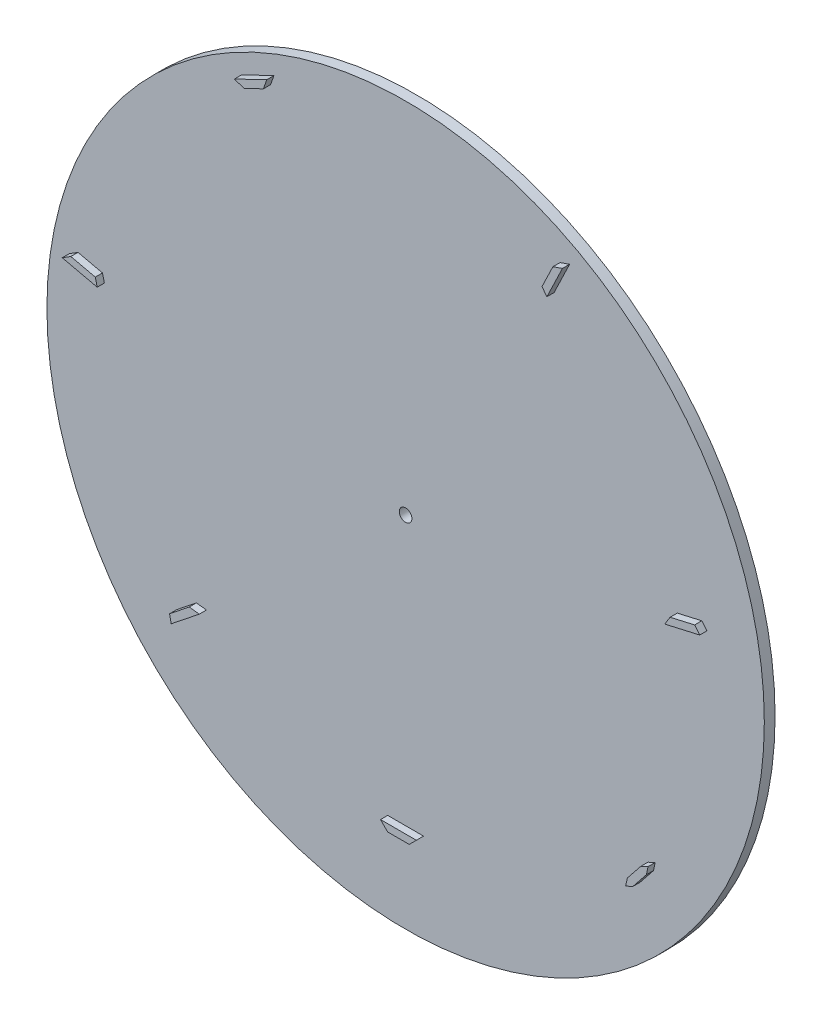
SolidWorks part; units mm, degrees
ref_plane "Front Plane" through (0, 0, 0) normal (0, 0, 1) x (1, 0, 0)
ref_plane "Top Plane" through (0, 0, 0) normal (0, 1, 0) x (1, 0, 0)
ref_plane "Right Plane" through (0, 0, 0) normal (1, 0, 0) x (0, 0, -1)
sketch "Sketch1" plane through (0, 0, 0) normal (0, 0, 1) x (1, 0, 0)
  circle A0 centre (0, 0) radius 100
  circle A1 centre (0, 0) radius 1.75
  dimension "D1" = 200
  dimension "D2" = 3.5
extrude "Boss-Extrude1" add sketch "Sketch1" along normal blind 3
sketch "Sketch2" plane through (0, 0, 3) normal (0, 0, 1) x (1, 0, 0)
  line L0 (0, 0) -> (0, -100) construction
  line L1 (0, 0) -> (-17.8557, -98.393) construction
  line L2 (0, 0) -> (-35.1375, -93.6235) construction
  line L3 (0, 0) -> (-51.2899, -85.8449) construction
  line L4 (0, 0) -> (-65.7939, -75.3071) construction
  line L5 (0, 0) -> (-78.1831, -62.349) construction
  line L6 (0, 0) -> (-88.0596, -47.3869) construction
  line L7 (0, 0) -> (-95.1057, -30.9017) construction
  line L8 (0, 0) -> (-99.095, -13.4233) construction
  line L9 (0, 0) -> (-99.8993, 4.4865) construction
  line L10 (0, 0) -> (-97.4928, 22.2521) construction
  line L11 (0, 0) -> (-91.9528, 39.3025) construction
  line L12 (0, 0) -> (-83.4573, 55.0897) construction
  line L13 (0, 0) -> (-72.2795, 69.1063) construction
  line L14 (0, 0) -> (-58.7785, 80.9017) construction
  line L15 (0, 0) -> (-43.3884, 90.0969) construction
  line L16 (0, 0) -> (-26.6037, 96.3963) construction
  line L17 (0, 0) -> (-8.9639, 99.5974) construction
  line L18 (0, 0) -> (8.9639, 99.5974) construction
  line L19 (0, 0) -> (26.6037, 96.3963) construction
  line L20 (0, 0) -> (43.3884, 90.0969) construction
  line L21 (0, 0) -> (58.7785, 80.9017) construction
  line L22 (0, 0) -> (72.2795, 69.1063) construction
  line L23 (0, 0) -> (83.4573, 55.0897) construction
  line L24 (0, 0) -> (91.9528, 39.3025) construction
  line L25 (0, 0) -> (97.4928, 22.2521) construction
  line L26 (0, 0) -> (99.8993, 4.4865) construction
  line L27 (0, 0) -> (99.095, -13.4233) construction
  line L28 (0, 0) -> (95.1057, -30.9017) construction
  line L29 (0, 0) -> (88.0596, -47.3869) construction
  line L30 (0, 0) -> (78.1831, -62.349) construction
  line L31 (0, 0) -> (65.7939, -75.3071) construction
  line L32 (0, 0) -> (51.2899, -85.8449) construction
  line L33 (0, 0) -> (35.1375, -93.6235) construction
  line L34 (0, 0) -> (17.8557, -98.393) construction
  line L35 (3, -77) -> (5, -75)
  line L36 (-5, -75) -> (5, -75)
  line L37 (-5, -75) -> (-5, -95) construction
  line L38 (-5, -95) -> (5, -95)
  line L39 (5, -75) -> (5, -95) construction
  line L40 (-3, -77) -> (3, -77)
  line L42 (-3, -93) -> (3, -93)
  line L44 (-3, -84) -> (3, -84)
  line L45 (-3, -84) -> (-3, -86) construction
  line L46 (-3, -86) -> (3, -86)
  line L47 (3, -84) -> (3, -86) construction
  line L48 (-3, -77) -> (-5, -75)
  line L49 (-3, -93) -> (-5, -95)
  line L50 (3, -93) -> (5, -95)
  line L51 (-3, -84) -> (-5, -85)
  line L52 (-5, -85) -> (-3, -86)
  line L53 (3, -84) -> (5, -85)
  line L54 (5, -85) -> (3, -86)
  line L55 (-3, -77) -> (-3, -84)
  line L56 (3, -77) -> (3, -84)
  line L57 (-3, -93) -> (-3, -86)
  line L58 (3, -93) -> (3, -86)
  line L59 (-5, -75) -> (-5, -85)
  line L60 (-5, -95) -> (-5, -85)
  line L61 (5, -75) -> (5, -85)
  line L62 (5, -95) -> (5, -85)
  line L63 (-61.7548, -42.8526) -> (-55.5199, -50.6709)
  line L64 (-61.7548, -42.8526) -> (-69.5731, -49.0875)
  line L65 (-62.0715, -45.6632) -> (-61.7548, -42.8526)
  line L66 (-62.0715, -45.6632) -> (-58.3306, -50.3542)
  line L67 (-58.3306, -50.3542) -> (-55.5199, -50.6709)
  line L68 (-55.5199, -50.6709) -> (-63.3382, -56.9058)
  line L69 (-58.3306, -50.3542) -> (-63.8034, -54.7186)
  line L70 (-62.0715, -45.6632) -> (-67.5443, -50.0276)
  line L71 (-67.5443, -50.0276) -> (-69.5731, -49.0875)
  line L72 (-69.5731, -49.0875) -> (-69.108, -51.2746)
  line L73 (-67.5443, -50.0276) -> (-63.8034, -54.7186)
  line L74 (-69.108, -51.2746) -> (-65.367, -55.9656)
  line L75 (-77.3914, -55.3224) -> (-69.5731, -49.0875)
  line L76 (-74.5808, -55.6391) -> (-69.108, -51.2746)
  line L77 (-74.5808, -55.6391) -> (-77.3914, -55.3224)
  line L78 (-77.3914, -55.3224) -> (-71.1565, -63.1407)
  line L79 (-74.5808, -55.6391) -> (-70.8399, -60.33)
  line L80 (-70.8399, -60.33) -> (-65.367, -55.9656)
  line L81 (-63.8034, -54.7186) -> (-63.3382, -56.9058)
  line L82 (-63.3382, -56.9058) -> (-65.367, -55.9656)
  line L83 (-71.1565, -63.1407) -> (-63.3382, -56.9058)
  line L84 (-70.8399, -60.33) -> (-71.1565, -63.1407)
  line L85 (-72.007, 21.5637) -> (-74.2322, 11.8144)
  line L86 (-72.007, 21.5637) -> (-81.7563, 23.7889)
  line L87 (-74.4019, 20.0589) -> (-72.007, 21.5637)
  line L88 (-74.4019, 20.0589) -> (-75.737, 14.2093)
  line L89 (-75.737, 14.2093) -> (-74.2322, 11.8144)
  line L90 (-74.2322, 11.8144) -> (-83.9815, 14.0396)
  line L91 (-75.737, 14.2093) -> (-82.5615, 15.767)
  line L92 (-74.4019, 20.0589) -> (-81.2264, 21.6165)
  line L93 (-81.2264, 21.6165) -> (-81.7563, 23.7889)
  line L94 (-81.7563, 23.7889) -> (-83.1762, 22.0616)
  line L95 (-81.2264, 21.6165) -> (-82.5615, 15.767)
  line L96 (-83.1762, 22.0616) -> (-84.5114, 16.212)
  line L97 (-91.5055, 26.0141) -> (-81.7563, 23.7889)
  line L98 (-90.0007, 23.6192) -> (-83.1762, 22.0616)
  line L99 (-90.0007, 23.6192) -> (-91.5055, 26.0141)
  line L100 (-91.5055, 26.0141) -> (-93.7308, 16.2648)
  line L101 (-90.0007, 23.6192) -> (-91.3359, 17.7697)
  line L102 (-91.3359, 17.7697) -> (-84.5114, 16.212)
  line L103 (-82.5615, 15.767) -> (-83.9815, 14.0396)
  line L104 (-83.9815, 14.0396) -> (-84.5114, 16.212)
  line L105 (-93.7308, 16.2648) -> (-83.9815, 14.0396)
  line L106 (-91.3359, 17.7697) -> (-93.7308, 16.2648)
  line L107 (-28.0364, 69.7421) -> (-37.0461, 65.4032)
  line L108 (-28.0364, 69.7421) -> (-32.3753, 78.7518)
  line L109 (-30.7061, 70.6763) -> (-28.0364, 69.7421)
  line L110 (-30.7061, 70.6763) -> (-36.112, 68.073)
  line L111 (-36.112, 68.073) -> (-37.0461, 65.4032)
  line L112 (-37.0461, 65.4032) -> (-41.385, 74.4129)
  line L113 (-36.112, 68.073) -> (-39.1491, 74.3797)
  line L114 (-30.7061, 70.6763) -> (-33.7433, 76.983)
  line L115 (-33.7433, 76.983) -> (-32.3753, 78.7518)
  line L116 (-32.3753, 78.7518) -> (-34.6111, 78.785)
  line L117 (-33.7433, 76.983) -> (-39.1491, 74.3797)
  line L118 (-34.6111, 78.785) -> (-40.0169, 76.1817)
  line L119 (-36.7141, 87.7615) -> (-32.3753, 78.7518)
  line L120 (-37.6483, 85.0918) -> (-34.6111, 78.785)
  line L121 (-37.6483, 85.0918) -> (-36.7141, 87.7615)
  line L122 (-36.7141, 87.7615) -> (-45.7238, 83.4226)
  line L123 (-37.6483, 85.0918) -> (-43.0541, 82.4885)
  line L124 (-43.0541, 82.4885) -> (-40.0169, 76.1817)
  line L125 (-39.1491, 74.3797) -> (-41.385, 74.4129)
  line L126 (-41.385, 74.4129) -> (-40.0169, 76.1817)
  line L127 (-45.7238, 83.4226) -> (-41.385, 74.4129)
  line L128 (-43.0541, 82.4885) -> (-45.7238, 83.4226)
  line L129 (37.0461, 65.4032) -> (28.0364, 69.7421)
  line L130 (37.0461, 65.4032) -> (41.385, 74.4129)
  line L131 (36.112, 68.073) -> (37.0461, 65.4032)
  line L132 (36.112, 68.073) -> (30.7061, 70.6763)
  line L133 (30.7061, 70.6763) -> (28.0364, 69.7421)
  line L134 (28.0364, 69.7421) -> (32.3753, 78.7518)
  line L135 (30.7061, 70.6763) -> (33.7433, 76.983)
  line L136 (36.112, 68.073) -> (39.1491, 74.3797)
  line L137 (39.1491, 74.3797) -> (41.385, 74.4129)
  line L138 (41.385, 74.4129) -> (40.0169, 76.1817)
  line L139 (39.1491, 74.3797) -> (33.7433, 76.983)
  line L140 (40.0169, 76.1817) -> (34.6111, 78.785)
  line L141 (45.7238, 83.4226) -> (41.385, 74.4129)
  line L142 (43.0541, 82.4885) -> (40.0169, 76.1817)
  line L143 (43.0541, 82.4885) -> (45.7238, 83.4226)
  line L144 (45.7238, 83.4226) -> (36.7141, 87.7615)
  line L145 (43.0541, 82.4885) -> (37.6483, 85.0918)
  line L146 (37.6483, 85.0918) -> (34.6111, 78.785)
  line L147 (33.7433, 76.983) -> (32.3753, 78.7518)
  line L148 (32.3753, 78.7518) -> (34.6111, 78.785)
  line L149 (36.7141, 87.7615) -> (32.3753, 78.7518)
  line L150 (37.6483, 85.0918) -> (36.7141, 87.7615)
  line L151 (74.2322, 11.8144) -> (72.007, 21.5637)
  line L152 (74.2322, 11.8144) -> (83.9815, 14.0396)
  line L153 (75.737, 14.2093) -> (74.2322, 11.8144)
  line L154 (75.737, 14.2093) -> (74.4019, 20.0589)
  line L155 (74.4019, 20.0589) -> (72.007, 21.5637)
  line L156 (72.007, 21.5637) -> (81.7563, 23.7889)
  line L157 (74.4019, 20.0589) -> (81.2264, 21.6165)
  line L158 (75.737, 14.2093) -> (82.5615, 15.767)
  line L159 (82.5615, 15.767) -> (83.9815, 14.0396)
  line L160 (83.9815, 14.0396) -> (84.5114, 16.212)
  line L161 (82.5615, 15.767) -> (81.2264, 21.6165)
  line L162 (84.5114, 16.212) -> (83.1762, 22.0616)
  line L163 (93.7308, 16.2648) -> (83.9815, 14.0396)
  line L164 (91.3359, 17.7697) -> (84.5114, 16.212)
  line L165 (91.3359, 17.7697) -> (93.7308, 16.2648)
  line L166 (93.7308, 16.2648) -> (91.5055, 26.0141)
  line L167 (91.3359, 17.7697) -> (90.0007, 23.6192)
  line L168 (90.0007, 23.6192) -> (83.1762, 22.0616)
  line L169 (81.2264, 21.6165) -> (81.7563, 23.7889)
  line L170 (81.7563, 23.7889) -> (83.1762, 22.0616)
  line L171 (91.5055, 26.0141) -> (81.7563, 23.7889)
  line L172 (90.0007, 23.6192) -> (91.5055, 26.0141)
  line L173 (55.5199, -50.6709) -> (61.7548, -42.8526)
  line L174 (55.5199, -50.6709) -> (63.3382, -56.9058)
  line L175 (58.3306, -50.3542) -> (55.5199, -50.6709)
  line L176 (58.3306, -50.3542) -> (62.0715, -45.6632)
  line L177 (62.0715, -45.6632) -> (61.7548, -42.8526)
  line L178 (61.7548, -42.8526) -> (69.5731, -49.0875)
  line L179 (62.0715, -45.6632) -> (67.5443, -50.0276)
  line L180 (58.3306, -50.3542) -> (63.8034, -54.7186)
  line L181 (63.8034, -54.7186) -> (63.3382, -56.9058)
  line L182 (63.3382, -56.9058) -> (65.367, -55.9656)
  line L183 (63.8034, -54.7186) -> (67.5443, -50.0276)
  line L184 (65.367, -55.9656) -> (69.108, -51.2746)
  line L185 (71.1565, -63.1407) -> (63.3382, -56.9058)
  line L186 (70.8399, -60.33) -> (65.367, -55.9656)
  line L187 (70.8399, -60.33) -> (71.1565, -63.1407)
  line L188 (71.1565, -63.1407) -> (77.3914, -55.3224)
  line L189 (70.8399, -60.33) -> (74.5808, -55.6391)
  line L190 (74.5808, -55.6391) -> (69.108, -51.2746)
  line L191 (67.5443, -50.0276) -> (69.5731, -49.0875)
  line L192 (69.5731, -49.0875) -> (69.108, -51.2746)
  line L193 (77.3914, -55.3224) -> (69.5731, -49.0875)
  line L194 (74.5808, -55.6391) -> (77.3914, -55.3224)
  circle A0 centre (0, 0) radius 95 construction
  circle A1 centre (0, 0) radius 100 construction
  circle A2 centre (0, 0) radius 75 construction
  point P42 (0, 0)
  point P46 (0, -75)
  point P47 (0, -95)
  point P53 (0, -77)
  point P149 (0, 0)
  dimension "D2" = 190
  dimension "D3" = 20
  dimension "D4" = 10
  dimension "D5" = 6
  dimension "D6" = 16
  dimension "D7" = 2
  dimension "D1" = 35
  dimension "D8" = 7
extrude "Boss-Extrude2" add sketch "Sketch2" along normal blind 2 contours L48 L40 L35 L36 | L69 L81 L68 L67 | L102 L106 L105 L104 | L128 L123 L121 L122 | L143 L142 L138 L141 | L159 L158 L153 L152 | L192 L191 L183 L181 L182 L184
